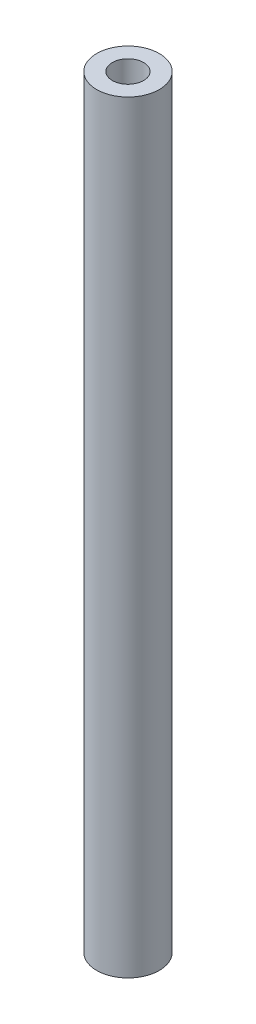
SolidWorks part; units mm, degrees
material "PTFE (general)"
ref_plane "Front Plane" through (0, 0, 0) normal (0, 0, 1) x (1, 0, 0)
ref_plane "Top Plane" through (0, 0, 0) normal (0, 1, 0) x (1, 0, 0)
ref_plane "Right Plane" through (0, 0, 0) normal (1, 0, 0) x (0, 0, -1)
sketch "Sketch1" plane through (0, 0, 0) normal (0, 1, 0) x (1, 0, 0)
  circle A0 centre (0, 0) radius 2
  circle A1 centre (0, 0) radius 1
  dimension "D1" = 4
  dimension "D2" = 2
extrude "Boss-Extrude1" add sketch "Sketch1" along normal mid plane 48.8 contours A0
sketch "Sketch2" [suppressed] plane through (0, 0, 0) normal (1, 0, 0) x (0, 0, -1)
  line L1 (2, 28.5) -> (-2, 28.5) construction
  circle A0 centre (-5.746, 30.5) radius 8
  dimension "D1" = 16
  dimension "D2" = 2
extrude "Cut-Extrude1" [suppressed] cut sketch "Sketch2" against normal mid plane 4
